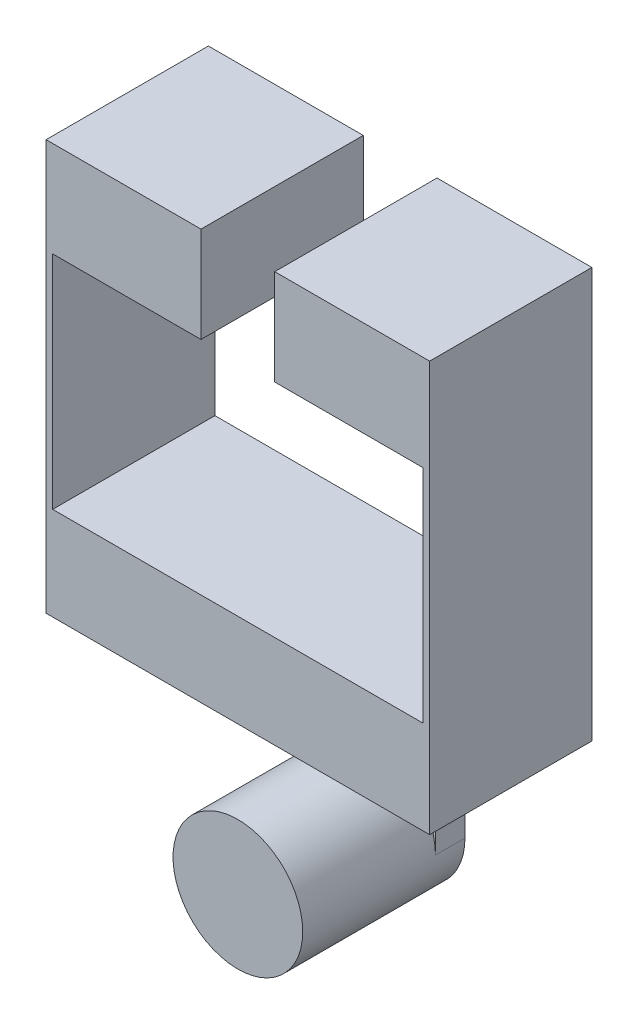
SolidWorks part; units mm, degrees
other "Markup1"
sketch "Sketch7" plane through (31.7043, 97.4003, 0) normal (0.5774, 0.5773, 0.5774) x (0.7071, 0, -0.7071)
material "ASTM A36 Steel"
ref_plane "Front Plane" through (0, 0, 0) normal (0, 0, 1) x (1, 0, 0)
ref_plane "Top Plane" through (0, 0, 0) normal (0, 1, 0) x (1, 0, 0)
ref_plane "Right Plane" through (0, 0, 0) normal (1, 0, 0) x (0, 0, -1)
sketch "Sketch1" plane through (0, 0, 0) normal (0, 0, 1) x (1, 0, 0)
  circle A0 centre (0, 0) radius 11.1628
  dimension "D1" = 22.3256
extrude "Boss-Extrude1" add sketch "Sketch1" against normal blind 25.4
sketch "Sketch2" plane through (0, 0, -25.4) normal (0, 0, -1) x (-1, 0, 0)
  line L0 (-11.1628, 0) -> (-11.1628, 25.4)
  line L1 (-11.1628, 25.4) -> (11.1628, 25.4)
  line L2 (11.1628, 25.4) -> (11.1628, 0)
  circle A0 centre (0, 0) radius 11.1628 construction
  arc A1 (11.1628, 0) -> (-11.1628, 0) centre (0, 0) ccw
  dimension "D1" = 22.3256
  dimension "D2" = 25.4
extrude "Boss-Extrude2" add sketch "Sketch2" against normal blind 2.54
ref_plane "Plane1" through (0, 25.4, 0) normal (0, 1, 0) x (1, 0, 0)
sketch "Sketch4" plane through (0, 25.4, 0) normal (0, 1, 0) x (1, 0, 0)
  line L0 (0, 0) -> (0, 55.2267) construction
  line L1 (-33.02, 0) -> (33.02, 0)
  line L2 (-33.02, 0) -> (-33.02, 25.4)
  line L3 (-33.02, 25.4) -> (33.02, 25.4)
  line L4 (33.02, 0) -> (33.02, 25.4)
  point P6 (0, 0)
  dimension "D1" = 25.4
  dimension "D2" = 66.04
extrude "Boss-Extrude3" add sketch "Sketch4" along normal blind 16.0644
sketch "Sketch5" plane through (0, 41.4644, 0) normal (0, 1, 0) x (1, 0, 0)
  line L0 (-33.02, 0) -> (33.02, 0) construction
  line L1 (-33.02, 25.4) -> (-31.8904, 25.4)
  line L2 (-33.02, 25.4) -> (-33.02, 0)
  line L3 (-33.02, 0) -> (-31.8904, 0)
  line L4 (-31.8904, 25.4) -> (-31.8904, 0)
  line L6 (33.02, 25.4) -> (31.8904, 25.4)
  line L7 (33.02, 25.4) -> (33.02, 0)
  line L8 (33.02, 0) -> (31.8904, 0)
  line L9 (31.8904, 25.4) -> (31.8904, 0)
  dimension "D1" = 1.1296
  dimension "D2" = 1.1296
extrude "Boss-Extrude4" add sketch "Sketch5" along normal blind 38.1
sketch "Sketch6" plane through (0, 79.5644, 0) normal (0, 1, 0) x (1, 0, 0)
  line L0 (31.8904, 25.4) -> (-31.8904, 25.4) construction
  line L1 (33.02, 0) -> (6.35, 0)
  line L2 (33.02, 0) -> (33.02, 25.4)
  line L3 (33.02, 25.4) -> (6.35, 25.4)
  line L4 (6.35, 0) -> (6.35, 25.4)
  line L5 (0, 0) -> (0, 25.4) construction
  line L6 (-6.35, 0) -> (-6.35, 25.4)
  line L7 (-33.02, 25.4) -> (-6.35, 25.4)
  line L8 (-33.02, 0) -> (-33.02, 25.4)
  line L9 (-33.02, 0) -> (-6.35, 0)
  dimension "D1" = 26.67
extrude "Boss-Extrude5" add sketch "Sketch6" along normal blind 16.4611
sketch "Sketch10" plane through (0, 0, -25.4) normal (0, 0, -1) x (-1, 0, 0)
  line L15 (11.1628, 0) -> (11.1628, 25.4)
  line L16 (11.1628, 25.4) -> (33.02, 25.4)
  line L17 (33.02, 25.4) -> (33.02, 96.0255)
  line L18 (33.02, 96.0255) -> (6.35, 96.0255)
  line L19 (6.35, 96.0255) -> (6.35, 79.5644)
  line L20 (6.35, 79.5644) -> (31.8904, 79.5644)
  line L21 (31.8904, 79.5644) -> (31.8904, 41.4644)
  line L22 (31.8904, 41.4644) -> (-31.8904, 41.4644)
  line L23 (-31.8904, 41.4644) -> (-31.8904, 79.5644)
  line L24 (-31.8904, 79.5644) -> (-6.35, 79.5644)
  line L25 (-6.35, 79.5644) -> (-6.35, 96.0255)
  line L26 (-6.35, 96.0255) -> (-33.02, 96.0255)
  line L27 (-33.02, 96.0255) -> (-33.02, 25.4)
  line L28 (-33.02, 25.4) -> (-11.1628, 25.4)
  line L29 (-11.1628, 25.4) -> (-11.1628, 0)
  line L30 (11.1628, 0) -> (11.1628, 25.4)
  line L31 (11.1628, 25.4) -> (33.02, 25.4)
  line L32 (33.02, 25.4) -> (33.02, 96.0255)
  line L33 (33.02, 96.0255) -> (6.35, 96.0255)
  line L34 (6.35, 96.0255) -> (6.35, 79.5644)
  line L35 (6.35, 79.5644) -> (31.8904, 79.5644)
  line L36 (31.8904, 79.5644) -> (31.8904, 41.4644)
  line L37 (31.8904, 41.4644) -> (-31.8904, 41.4644)
  line L38 (-31.8904, 41.4644) -> (-31.8904, 79.5644)
  line L39 (-31.8904, 79.5644) -> (-6.35, 79.5644)
  line L40 (-6.35, 79.5644) -> (-6.35, 96.0255)
  line L41 (-6.35, 96.0255) -> (-33.02, 96.0255)
  line L42 (-33.02, 96.0255) -> (-33.02, 25.4)
  line L43 (-33.02, 25.4) -> (-11.1628, 25.4)
  line L44 (-11.1628, 25.4) -> (-11.1628, 0)
  arc A1 (-11.1628, 0) -> (11.1628, 0) centre (0, 0) ccw
  arc A2 (-11.1628, 0) -> (11.1628, 0) centre (0, 0) ccw
  dimension "D1" = 0
extrude "Boss-Extrude8" add sketch "Sketch10" along normal blind 2.54
equation "\"F\"= 600"
equation "\"E\"= 29000000"
equation "\"Sy\"= 36000"
equation "\"Tallow\"= 9000"
equation "\"La\"= 1in"
equation "\"SF\"= 4"
equation "\"Z\"=  ( \"SF\" *  ( 2 * \"F\" )  * \"La\" )  /  ( 2 * \"Sy\" ) "
equation "\"Ra\"= ( ( \"Z\" / pi ) * 4 ) ^ ( 1 / 3 )"
equation "\"Bw\"= .879in"
equation "\"Ba\"= ( \"SF\" * \"F\" ) / ( \"Sy\" )"
equation "\"Tb\"= \"Ba\" / \"Bw\""
equation "\"Cw\"=2.6"
equation "\"Ct\"= 1"
equation "\"Ca\"= ( \"SF\" * ( 2 * \"F\" ) ) / \"Sy\""
equation "\"Ch\"= ( \"Z\" * 6 ) ^ ( 1 / 2 )"
equation "\"Da\"= ( \"F\" * \"SF\" ) / ( \"Sy\" )"
equation "\"Dh\"= 1.499"
equation "\"Dw\"= \"Da\" / \"Dh\""
equation "\"Ea\"= ( \"F\" * \"SF\" ) / ( \"Sy\" )"
equation "\"Ew\"=1.05"
equation "\"Ad\"= \"Ra\" * 2"
equation "\"D1@Sketch1\"=\"Ad\""
equation "\"D1@Boss-Extrude1\"=\"La\""
equation "\"D1@Boss-Extrude2\"=.1"
equation "\"D1@Sketch2\"=\"Ad\""
equation "\"D2@Sketch4\"=\"Cw\""
equation "\"D1@Boss-Extrude3\"=\"Ch\""
equation "\"D1@Sketch5\"=\"Dw\""
equation "\"D2@Sketch5\"=\"Dw\""
equation "\"D1@Sketch6\"=\"Ew\""
equation "\"D1@Boss-Extrude5\"=\"Eh\""
equation "\"Ehtop\"= ( 6 * \"F\" * \"Ew\" * \"SF\" )"
equation "\"Ehbottom\"= ( 1 * \"Sy\" )"
equation "\"Eh\"= ( \"Ehtop\" / \"Ehbottom\" ) ^ ( 1 / 2 )"
